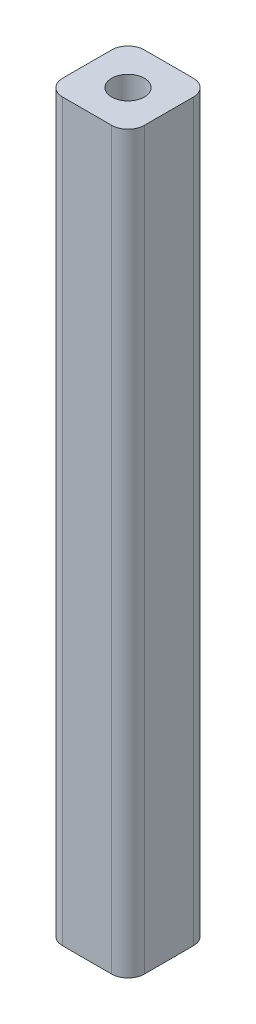
SolidWorks part; units mm, degrees
ref_plane "前视基准面" through (0, 0, 0) normal (0, 0, 1) x (1, 0, 0)
ref_plane "上视基准面" through (0, 0, 0) normal (0, 1, 0) x (1, 0, 0)
ref_plane "右视基准面" through (0, 0, 0) normal (1, 0, 0) x (0, 0, -1)
sketch "草图1" plane through (0, 0, 0) normal (0, 1, 0) x (1, 0, 0)
  line L1 (5, -5) -> (-5, -5)
  line L2 (5, -5) -> (5, 5)
  line L3 (5, 5) -> (-5, 5)
  line L4 (-5, -5) -> (-5, 5)
  line L5 (5, -5) -> (-5, 5) construction
  line L6 (5, 5) -> (-5, -5) construction
  point P0 (0, 0)
  dimension "D1" = 10
  dimension "D2" = 10
extrude "凸台-拉伸1" add sketch "草图1" along normal blind 90
sketch "草图2" plane through (0, 90, 0) normal (0, 1, 0) x (1, 0, 0)
  circle A0 centre (0, 0) radius 2
  dimension "D1" = 4
extrude "切除-拉伸1" cut sketch "草图2" against normal blind 10
sketch "草图4" plane through (0, 0, 0) normal (0, -1, 0) x (1, 0, 0)
  circle A0 centre (0, 0) radius 2
  dimension "D1" = 4
extrude "切除-拉伸2" cut sketch "草图4" against normal blind 10
fillet "圆角1" radius 2 4 edges at (-5, 45, 5) (5, 45, 5) (5, 45, -5) (-5, 45, -5)
